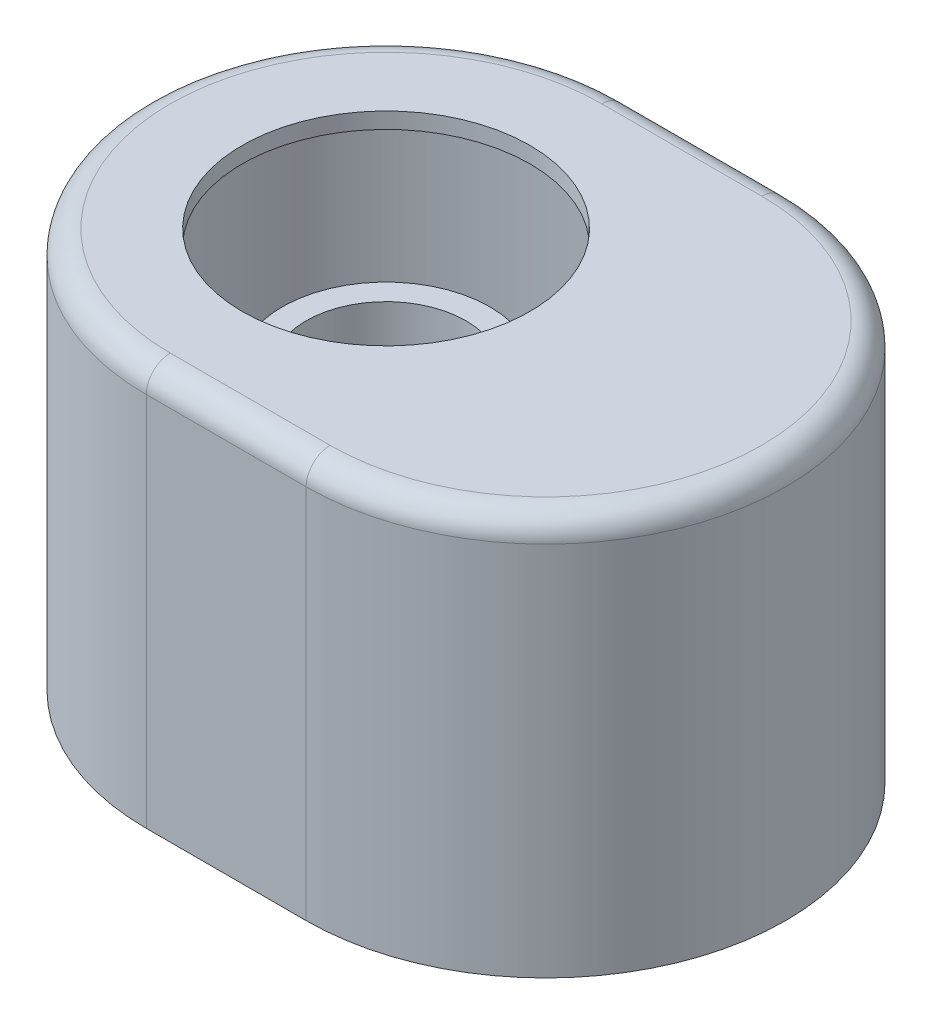
SolidWorks part; units mm, degrees
ref_plane "前视基准面" through (0, 0, 0) normal (0, 0, 1) x (1, 0, 0)
ref_plane "上视基准面" through (0, 0, 0) normal (0, 1, 0) x (1, 0, 0)
ref_plane "右视基准面" through (0, 0, 0) normal (1, 0, 0) x (0, 0, -1)
other "Configuration Table"
sketch "草图1" plane through (0, 0, 0) normal (0, 1, 0) x (1, 0, 0)
  line L0 (0, 0) -> (20, 0) construction
  line L1 (0, 30) -> (20, 30)
  line L2 (0, -30) -> (20, -30)
  arc A0 (0, 30) -> (0, -30) centre (0, 0) ccw
  arc A1 (20, -30) -> (20, 30) centre (20, 0) ccw
  point P3 (10, 0)
  dimension "D2" = 60
  dimension "D1" = 20
extrude "凸台-拉伸1" add sketch "草图1" along normal blind 50
fillet "圆角1" radius 3 4 edges at (10, 50, -30) (50, 50, 0) (10, 50, 30) (-30, 50, 0)
shell "抽壳1" thickness 2
sketch "草图2" plane through (0, 50, 0) normal (0, 1, 0) x (1, 0, 0)
  circle A0 centre (0, 0) radius 18
  dimension "D1" = 36
extrude "切除-拉伸1" cut sketch "草图2" against normal up to next
sketch "草图3" plane through (0, 0, 0) normal (0, 0, 1) x (1, 0, 0)
  line L0 (0, 0) -> (0, 53.4494) construction
  line L1 (0, 35) -> (-10, 35) construction
  line L2 (-10, 35) -> (-13, 35)
  line L3 (-13, 35) -> (-13, 27.6329)
  line L4 (-13, 27.6329) -> (-9.5, 21.6329)
  line L5 (-9.5, 21.6329) -> (-9.5, 15)
  line L6 (-9.5, 15) -> (-6.5, 15)
  line L8 (-4.5, 21) -> (-8, 27)
  line L9 (-8, 29) -> (-10, 29)
  line L10 (-8, 27) -> (-8, 29)
  line L11 (-10, 29) -> (-10, 35)
  line L12 (-6.5, 15) -> (-6.5, 19)
  line L13 (-6.5, 19) -> (-4.5, 19)
  line L14 (-4.5, 19) -> (-4.5, 21)
  line L15 (18, 50) -> (-18, 50) construction
  point P13 (-9, 29)
  dimension "D1" = 3
  dimension "D2" = 4
  dimension "D3" = 13
  dimension "D4" = 2
  dimension "D5" = 10
  dimension "D6" = 3
  dimension "D7" = 6
  dimension "D8" = 2
  dimension "D9" = 2
  dimension "D10" = 4
  dimension "D11" = 15
  dimension "D12" = 2
  dimension "D13" = 20
revolve "旋转1" add sketch "草图3" angle 360 about L0
